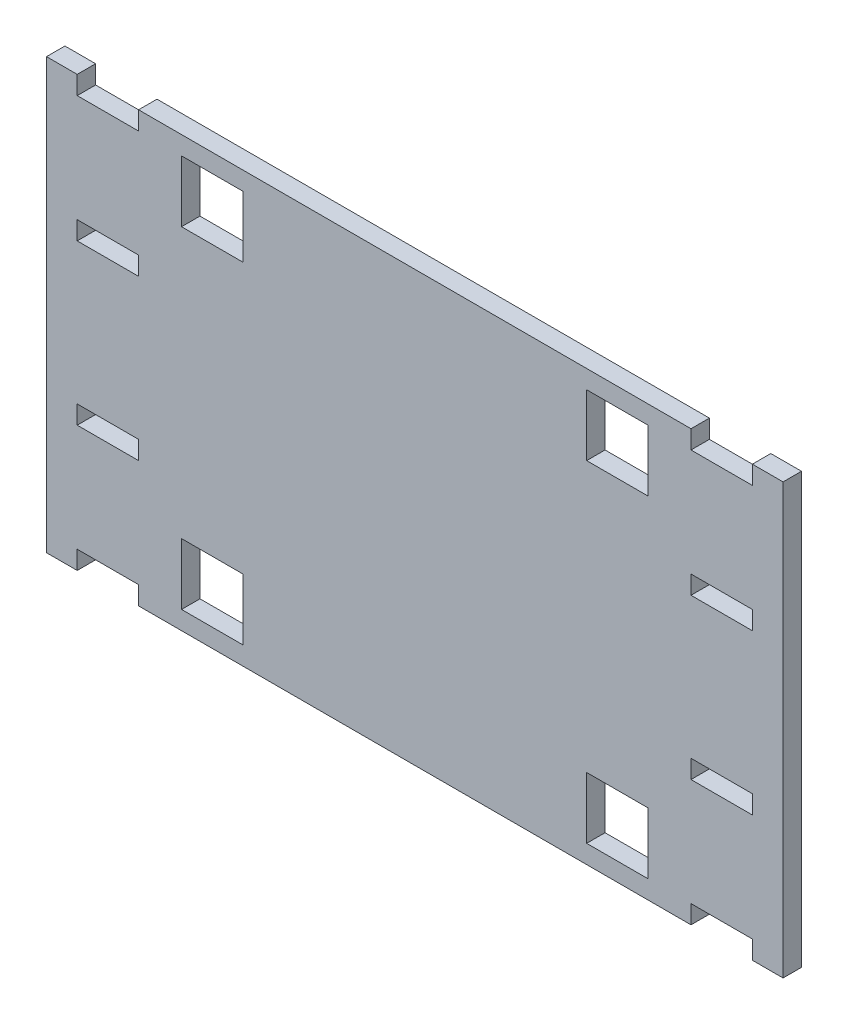
SolidWorks part; units mm, degrees
ref_plane "Front Plane" through (0, 0, 0) normal (0, 0, 1) x (1, 0, 0)
ref_plane "Top Plane" through (0, 0, 0) normal (0, 1, 0) x (1, 0, 0)
ref_plane "Right Plane" through (0, 0, 0) normal (1, 0, 0) x (0, 0, -1)
sketch "Sketch2" plane through (0, 0, 0) normal (0, 0, 1) x (1, 0, 0)
  line L1 (-60, 35) -> (60, 35)
  line L2 (-60, 35) -> (-60, -35)
  line L3 (-60, -35) -> (60, -35)
  line L4 (60, 35) -> (60, -35)
  line L5 (-60, 35) -> (60, -35) construction
  line L6 (-60, -35) -> (60, 35) construction
  point P0 (0, 0)
  dimension "D1" = 120
  dimension "D2" = 70
extrude "Boss-Extrude1" add sketch "Sketch2" along normal blind 3
sketch "Sketch3" plane through (0, 0, 0) normal (0, 0, -1) x (-1, 0, 0)
  line L0 (-61.3588, 0) -> (66.3745, 0) construction
  line L1 (-60, 35) -> (60, 35) construction
  line L2 (-55, 35) -> (-45, 35)
  line L3 (-55, 35) -> (-55, 32)
  line L4 (-55, 32) -> (-45, 32)
  line L5 (-45, 35) -> (-45, 32)
  line L6 (-60, -35) -> (-60, 35) construction
  dimension "D1" = 3
  dimension "D2" = 10
  dimension "D3" = 5
extrude "Cut-Extrude1" cut sketch "Sketch3" against normal through all and the other way through all
pattern_linear "LPattern1" count 2 spacing 20.5 along (0, -1, 0) of "Cut-Extrude1"
sketch "Sketch4" plane through (0, 0, 0) normal (0, 0, -1) x (-1, 0, 0)
  line L0 (-45, 35) -> (60, 35) construction
  line L1 (-38, 32) -> (-28, 32)
  line L2 (-38, 32) -> (-38, 22)
  line L3 (-38, 22) -> (-28, 22)
  line L4 (-28, 32) -> (-28, 22)
  line L5 (-45, 14.5) -> (-45, 11.5) construction
  point P8 (-45, 13)
  dimension "D1" = 10
  dimension "D2" = 10
  dimension "D3" = 3
  dimension "D4" = 7
extrude "Cut-Extrude2" cut sketch "Sketch4" against normal through all
sketch "Sketch5" plane through (0, 0, 0) normal (0, 0, -1) x (-1, 0, 0)
  line L0 (60, 35) -> (60, -35) construction
  line L1 (1.65, 0) -> (-1.65, 0) construction
  circle A0 centre (55, 15) radius 1.5
  circle A1 centre (31, 15) radius 1.5
  dimension "D1" = 3
  dimension "D2" = 5
  dimension "D4" = 24
  dimension "D5" = 15
  dimension "D3" = 15
extrude "Cut-Extrude3" [suppressed] cut sketch "Sketch5" against normal through all
mirror "Mirror1" about plane through (0, 0, 0) normal (0, 1, 0) of "Cut-Extrude3", "Cut-Extrude2", "Cut-Extrude1", "LPattern1"
mirror "Mirror2" about plane through (0, 0, 0) normal (1, 0, 0) of "Mirror1", "LPattern1", "Cut-Extrude1", "Cut-Extrude2"
